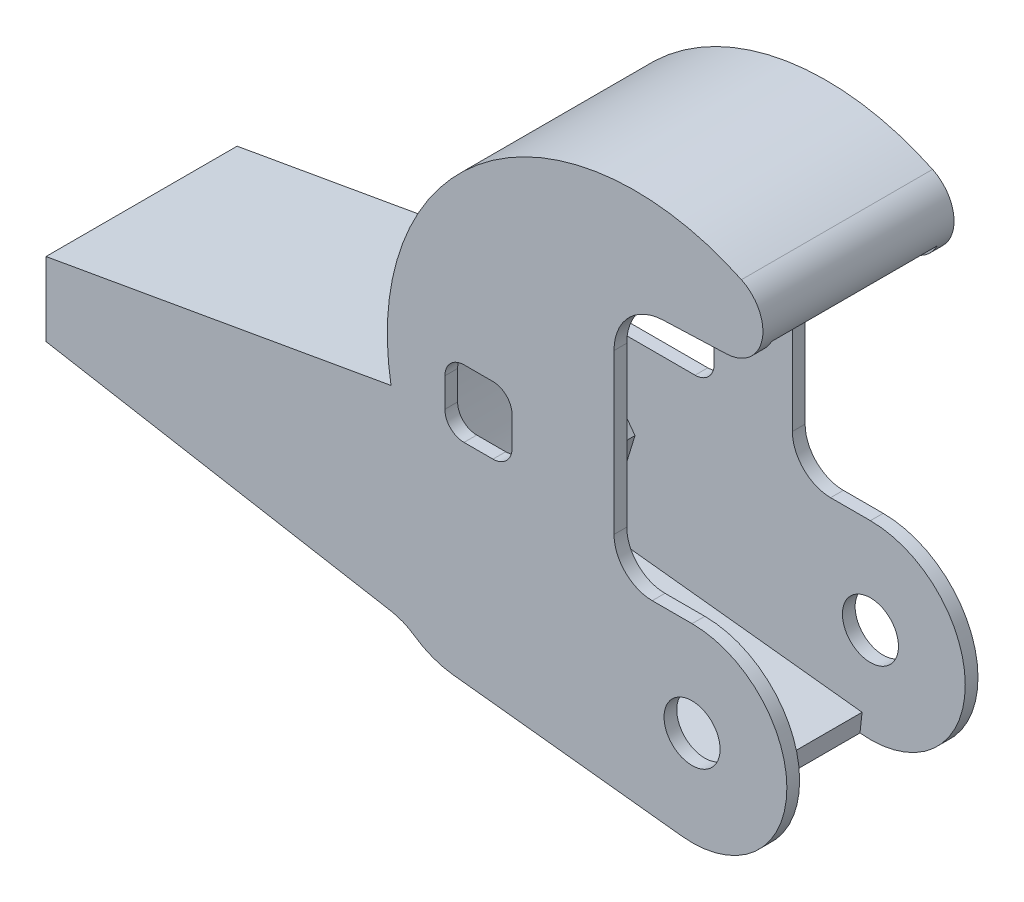
SolidWorks part; units mm, degrees
ref_plane "Front Plane" through (0, 0, 0) normal (0, 0, 1) x (1, 0, 0)
ref_plane "Top Plane" through (0, 0, 0) normal (0, 1, 0) x (1, 0, 0)
ref_plane "Right Plane" through (0, 0, 0) normal (1, 0, 0) x (0, 0, -1)
sketch "Sketch1" plane through (0, 0, 0) normal (0, 0, 1) x (1, 0, 0)
  line L0 (-41.8881, 5.785) -> (12.2763, 15.3356)
  line L6 (12.2763, -15.3356) -> (-41.8881, -5.785)
  line L7 (-41.8881, -5.785) -> (-41.8881, 5.785)
  line L8 (-41.8881, 0) -> (41.8881, 0) construction
  line L10 (64.9626, 45.9573) -> (54.97, 45.5743)
  line L11 (47.2763, 37.5802) -> (47.2763, 12.5802)
  line L12 (53.2763, 6.5802) -> (59.5263, 6.5802)
  line L14 (22.0237, -19.1314) -> (57.8876, -23.1034)
  arc A8 (12.2763, 15.3356) -> (67.2763, 57.2103) centre (50.5755, 22.0888) cw
  arc A10 (54.97, 45.5743) -> (47.2763, 37.5802) centre (55.2763, 37.5802) ccw
  arc A11 (47.2763, 12.5802) -> (53.2763, 6.5802) centre (53.2763, 12.5802) ccw
  arc A13 (22.0237, -19.1314) -> (15.9158, -16.8375) centre (23.4812, -5.9718) cw
  arc A14 (15.9158, -16.8375) -> (12.2763, -15.3356) centre (10.6874, -24.3466) ccw
  arc A19 (67.2763, 57.2103) -> (64.9626, 45.9573) centre (64.7361, 51.8682) cw
  arc A20 (59.5263, 6.5802) -> (57.8876, -23.1034) centre (59.5263, -8.3068) cw
  point P12 (0, 0)
  dimension "D7" = 38.89
  dimension "D9" = 8
  dimension "D11" = 9.15
  dimension "D12" = 13.24
  dimension "D18" = 6
  dimension "D1" = 55
  dimension "D2" = 11.57
  dimension "D3" = 100
  dimension "D4" = 55
  dimension "D5" = 10
  dimension "D8" = 23.3
  dimension "D10" = 25
  dimension "D15" = 6.25
  dimension "D16" = 22.39
  dimension "D6" = 35
extrude "Boss-Extrude1" add sketch "Sketch1" along normal blind 30
sketch "Sketch2" plane through (0, 0, 30) normal (0, 0, 1) x (1, 0, 0)
  circle A0 centre (59.5263, -8.3068) radius 4.4
  arc A1 (57.8876, -23.1034) -> (59.5263, 6.5802) centre (59.5263, -8.3068) ccw construction
  dimension "D1" = 8.8
extrude "Cut-Extrude1" cut sketch "Sketch2" against normal through all
ref_plane "Plane1" through (70, 0, 0) normal (1, 0, 0) x (0, 0, -1)
sketch "Sketch4" plane through (70, 0, 0) normal (1, 0, 0) x (0, 0, -1)
  line L1 (-28, 51.4688) -> (-2, 51.4688)
  line L2 (-28, 51.4688) -> (-28, -1.7867)
  line L3 (-28, -1.7867) -> (-2, -1.7867)
  line L4 (-2, 51.4688) -> (-2, -1.7867)
  line L6 (0, 12.5802) -> (0, 37.5802) construction
  line L7 (-30, 12.5802) -> (-30, 37.5802) construction
  dimension "D1" = 2
  dimension "D2" = 2
extrude "Cut-Extrude2" cut sketch "Sketch4" against normal blind 40
ref_plane "Plane2" through (0, 0, 15) normal (0, 0, 1) x (1, 0, 0)
sketch "Sketch5" plane through (0, 0, 15) normal (0, 0, 1) x (1, 0, 0)
  line L0 (30, -1.7867) -> (70, -1.7867) construction
  line L1 (30, 51.4688) -> (30, -1.7867) construction
  line L2 (63.4888, -1.7867) -> (35, -1.7867)
  line L4 (30, 51.4688) -> (30, 3.2133)
  arc A0 (67.2763, 57.2103) -> (12.2763, 15.3356) centre (50.5755, 22.0888) ccw construction
  arc A1 (67.2763, 57.2103) -> (12.2763, 15.3356) centre (50.5755, 22.0888) ccw
  arc A2 (30, 51.4688) -> (27.1602, -5.082) centre (50.5755, 22.0888) ccw
  arc A3 (30, 3.2133) -> (35, -1.7867) centre (35, 3.2133) ccw
  spline S0 degree 3 poles (27.1602, -5.082) (28.0949, -5.8876) (30.5867, -8.1946) (37.2387, -9.9176) (48.9595, -8.5402) (58.3946, -6.2386) (63.4888, -1.7867) knots 0 0 0 0 0.093404 0.26112 0.503691 1 1 1 1
  dimension "D1" = 5
extrude "Cut-Extrude3" cut sketch "Sketch5" against normal mid plane 26 contours A2 S0 L2 A3 L4
sketch "Sketch6" plane through (0, 0, 15) normal (0, 0, 1) x (1, 0, 0)
  line L5 (32, 24.5949) -> (20, 24.5949)
  line L6 (17, 21.5949) -> (17, 15.5949)
  line L7 (20, 12.5949) -> (32, 12.5949)
  line L8 (35, 15.5949) -> (35, 21.5949)
  line L9 (70, -16.5) -> (70, 16.5) construction
  arc A0 (20, 24.5949) -> (17, 21.5949) centre (20, 21.5949) ccw
  arc A1 (17, 15.5949) -> (20, 12.5949) centre (20, 15.5949) ccw
  arc A2 (32, 12.5949) -> (35, 15.5949) centre (32, 15.5949) ccw
  arc A3 (35, 21.5949) -> (32, 24.5949) centre (32, 21.5949) ccw
  dimension "D4" = 3
  dimension "D1" = 12
  dimension "D2" = 6
  dimension "D3" = 35
extrude "Cut-Extrude4" cut sketch "Sketch6" against normal blind 22
sketch "Sketch7" plane through (0, 0, 15) normal (0, 0, 1) x (1, 0, 0)
  line L0 (32, 12.5949) -> (20, 12.5949) construction
  line L1 (35, 21.5949) -> (35, 15.5949) construction
  line L2 (17, 15.5949) -> (17, 21.5949) construction
  line L3 (20, 24.5949) -> (32, 24.5949) construction
  line L4 (32, 12.5949) -> (20, 12.5949) construction
  line L5 (35, 21.5949) -> (35, 15.5949) construction
  line L6 (17, 15.5949) -> (17, 21.5949) construction
  line L7 (20, 24.5949) -> (32, 24.5949) construction
  line L8 (28.275, 23.8699) -> (23.725, 23.8699)
  line L9 (20.725, 20.8699) -> (20.725, 16.3199)
  line L10 (23.725, 13.3199) -> (28.275, 13.3199)
  line L11 (31.275, 16.3199) -> (31.275, 20.8699)
  line L12 (35, 18.5949) -> (20.725, 18.5949) construction
  line L13 (26, 23.8699) -> (26, 12.5949) construction
  arc A0 (17, 15.5949) -> (20, 12.5949) centre (20, 15.5949) ccw construction
  arc A1 (32, 12.5949) -> (35, 15.5949) centre (32, 15.5949) ccw construction
  arc A2 (20, 24.5949) -> (17, 21.5949) centre (20, 21.5949) ccw construction
  arc A3 (35, 21.5949) -> (32, 24.5949) centre (32, 21.5949) ccw construction
  arc A4 (17, 15.5949) -> (20, 12.5949) centre (20, 15.5949) ccw construction
  arc A5 (32, 12.5949) -> (35, 15.5949) centre (32, 15.5949) ccw construction
  arc A6 (20, 24.5949) -> (17, 21.5949) centre (20, 21.5949) ccw construction
  arc A7 (35, 21.5949) -> (32, 24.5949) centre (32, 21.5949) ccw construction
  arc A8 (23.725, 23.8699) -> (20.725, 20.8699) centre (23.725, 20.8699) ccw
  arc A9 (20.725, 16.3199) -> (23.725, 13.3199) centre (23.725, 16.3199) ccw
  arc A10 (28.275, 13.3199) -> (31.275, 16.3199) centre (28.275, 16.3199) ccw
  arc A11 (31.275, 20.8699) -> (28.275, 23.8699) centre (28.275, 20.8699) ccw
  dimension "D2" = 3
  dimension "D1" = 4.55
extrude "Cut-Extrude5" cut sketch "Sketch7" along normal blind 29
sketch "Sketch9" plane through (0, 0, 15) normal (0, 0, 1) x (1, 0, 0)
  line L0 (63.4888, -1.7867) -> (70, -1.7867) construction
  line L1 (63.4888, -1.7867) -> (66.9588, -1.7867)
  line L2 (22.0237, -19.1314) -> (57.8876, -23.1034) construction
  line L3 (22.0237, -19.1314) -> (57.8876, -23.1034)
  line L4 (22.5741, -14.1618) -> (58.438, -18.1337)
  line L5 (22.5741, -0.3267) -> (18.7728, -12.7342)
  line L6 (27.1602, -5.082) -> (22.5741, -0.3267)
  circle A0 centre (59.5263, -8.3068) radius 4.4 construction
  arc A2 (55.5602, -6.4016) -> (60.4814, -4.0117) centre (59.5263, -8.3068) ccw
  arc A4 (15.9158, -16.8375) -> (22.0237, -19.1314) centre (23.4812, -5.9718) ccw construction
  arc A6 (15.9158, -16.8375) -> (22.0237, -19.1314) centre (23.4812, -5.9718) ccw
  arc A8 (18.7728, -12.7342) -> (22.5741, -14.1618) centre (23.4812, -5.9718) ccw
  arc A9 (58.438, -18.1337) -> (66.9588, -1.7867) centre (59.5263, -8.3068) ccw
  arc A10 (30, 51.4688) -> (27.1602, -5.082) centre (50.5755, 22.0888) ccw construction
  arc A11 (58.438, -18.1337) -> (59.5263, 1.5802) centre (59.5263, -8.3068) ccw construction
  arc A12 (57.8876, -23.1034) -> (59.5263, 6.5802) centre (59.5263, -8.3068) ccw construction
  spline S0 degree 3 poles (1712.7818, -3641.3632) (-1875.2136, 3600.7131) (1912.105, -3638.779) (-1487.7557, 3680.8069) knots -5.310123 -5.310123 -5.310123 -5.310123 6.125598 6.125598 6.125598 6.125598 only from (60.4814, -4.0117) to (63.4888, -1.7867) construction
  spline S1 degree 3 poles (-2619.7238, -3002.4652) (58.7311, 145.2058) (0.1224, -0.3036) (37.2387, -9.9176) (115.2129, -0.7546) (183.6254, 82.4037) (-1486.9142, 3678.9951) knots -2.306777 -2.306777 -2.306777 -2.306777 0.093404 0.26112 0.503691 6.124654 6.124654 6.124654 6.124654 only from (27.1602, -5.082) to (55.5602, -6.4016) construction
  spline S2 degree 3 poles (60.4814, -4.0117) (61.5228, -3.3628) (62.5279, -2.6265) (63.4888, -1.7867) knots 0.906384 0.906384 0.906384 0.906384 1 1 1 1
  spline S3 degree 3 poles (27.1602, -5.082) (28.0949, -5.8876) (30.5867, -8.1946) (37.2387, -9.9176) (45.9276, -8.8965) (52.3935, -7.5809) (55.5602, -6.4016) knots 0 0 0 0 0.093404 0.26112 0.503691 0.765484 0.765484 0.765484 0.765484
  dimension "D1" = 5
extrude "Cut-Extrude6" cut sketch "Sketch9" against normal mid plane 26 contours S3 L6 L5 A8 L4 A9 L1 S2 A2
sketch "Sketch10" plane through (0, 0, 15) normal (0, 0, 1) x (1, 0, 0)
  line L0 (70, -2.5405) -> (70, -17.4307)
  line L1 (70, -16.5) -> (70, 16.5) construction
  line L2 (66.9588, -1.7867) -> (70, -1.7867) construction
  line L3 (66.9588, -1.7867) -> (70, -1.7867)
  line L4 (22.5741, -14.1618) -> (58.438, -18.1337) construction
  line L5 (22.5741, -14.1618) -> (58.438, -18.1337)
  line L6 (22.354, -16.1496) -> (58.2178, -20.1216)
  line L7 (70.4947, -3.7246) -> (70.4947, -3.7246)
  line L8 (17.63, -14.3755) -> (18.7728, -12.7342)
  line L9 (70, -1.7867) -> (70.4947, -3.7246)
  arc A0 (58.438, -18.1337) -> (66.9588, -1.7867) centre (59.5263, -8.3068) ccw construction
  arc A1 (58.438, -18.1337) -> (66.9588, -1.7867) centre (59.5263, -8.3068) ccw
  arc A2 (18.7728, -12.7342) -> (22.5741, -14.1618) centre (23.4812, -5.9718) ccw construction
  arc A3 (18.7728, -12.7342) -> (22.5741, -14.1618) centre (23.4812, -5.9718) ccw
  arc A4 (17.63, -14.3755) -> (22.354, -16.1496) centre (23.4812, -5.9718) ccw
  arc A5 (58.2178, -20.1216) -> (70.4947, -3.7246) centre (59.5263, -8.3068) ccw
  dimension "D1" = 2
extrude "Cut-Extrude7" cut sketch "Sketch10" against normal mid plane 26 contours L9 L3 A1 L5 A3 L8 A4 L6 A5
ref_plane "Plane3" through (57.8876, -23.1034, 0) normal (0.9939, -0.1101, 0) x (0, 0, -1)
sketch "Sketch11" plane through (0, 0, 15) normal (0, 0, 1) x (1, 0, 0)
  line L1 (70, -1.7867) -> (70.4947, -3.7246) construction
  line L2 (70, -1.7867) -> (70, 0)
  line L3 (70, -1.7867) -> (70.4947, -3.7246)
  line L4 (58.2178, -20.1216) -> (57.8876, -23.1034)
  line L5 (70, -16.5) -> (70, 16.5) construction
  line L6 (70, 0) -> (71.8803, 0)
  line L7 (58.2178, -20.1216) -> (57.8876, -23.1034)
  arc A1 (58.2178, -20.1216) -> (70.4947, -3.7246) centre (59.5263, -8.3068) ccw construction
  arc A2 (57.8876, -23.1034) -> (59.5263, 6.5802) centre (59.5263, -8.3068) ccw construction
  arc A3 (58.2178, -20.1216) -> (70.4947, -3.7246) centre (59.5263, -8.3068) ccw
  arc A4 (57.8876, -23.1034) -> (71.8803, 0) centre (59.5263, -8.3068) ccw
extrude "Cut-Extrude8" cut sketch "Sketch11" against normal mid plane 26 contours L4 A4 L6 L2 L3 A3
sketch "Sketch12" plane through (0, 0, 15) normal (0, 0, 1) x (1, 0, 0)
  line L0 (70, 0) -> (70, 2.2727) construction
  line L1 (70, 0) -> (71.8803, 0) construction
  line L2 (70, 0) -> (70, 2.2727)
  line L3 (70, 0) -> (71.8803, 0)
  arc A0 (57.8876, -23.1034) -> (59.5263, 6.5802) centre (59.5263, -8.3068) ccw construction
  arc A1 (71.8803, 0) -> (70, 2.2727) centre (59.5263, -8.3068) ccw
extrude "Cut-Extrude9" cut sketch "Sketch12" against normal mid plane 26
equation "\"A\"= 55mm"
equation "\"D1@Sketch1\"=\"A\""
equation "\"D2@Sketch1\"=\"A\"*(11.57/55)"
equation "\"D7@Sketch1\"=\"A\"*(38.89/55)"
equation "\"D4@Sketch1\"=\"A\"*(55/55)"
equation "\"D5@Sketch1\"=\"A\"*(10/55)"
equation "\"D8@Sketch1\"=\"A\"*(23.3/55)"
equation "\"D9@Sketch1\"=\"A\"*(8/55)"
equation "\"D10@Sketch1\"=\"A\"*(25/55)"
equation "\"D12@Sketch1\"=\"A\"*(13.24/55)"
equation "\"D15@Sketch1\"=\"A\"*(6.25/55)"
equation "\"D18@Sketch1\"=\"A\"*(6/55)"
equation "\"D1@Sketch2\"=\"A\"*(8/50)"
equation "\"D1@Sketch4\"=\"A\"*(2/55)"
equation "\"D2@Sketch4\"=\"A\"*(2/55)"
equation "\"D1@Cut-Extrude3\"=\"A\"*(26/55)"
equation "\"D2@Sketch6\"=\"A\"*(6/55)"
equation "\"D1@Sketch6\"=\"A\"*(12/55)"
equation "\"D3@Sketch6\"=\"A\"*(35/55)"
equation "\"D4@Sketch6\"=\"A\"*(3/55)"
equation "\"D6@Sketch1\"=\"A\"*(35/55)"
equation "\"D1@Sketch7\"=\"A\"*(4.55/55)"
equation "\"D2@Sketch7\"=\"A\"*(3/55)"
